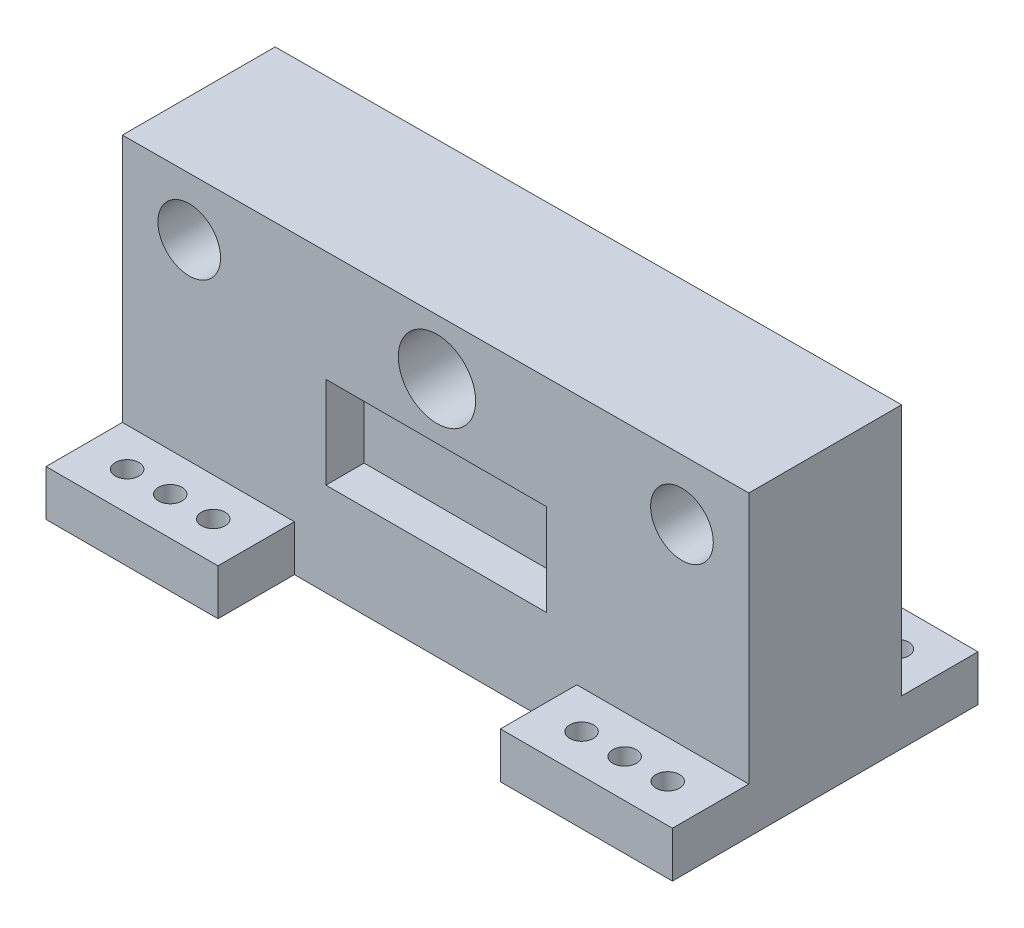
SolidWorks part; units mm, degrees
ref_plane "Спереди" through (0, 0, 0) normal (0, 0, 1) x (1, 0, 0)
ref_plane "Сверху" through (0, 0, 0) normal (0, 1, 0) x (1, 0, 0)
ref_plane "Справа" through (0, 0, 0) normal (1, 0, 0) x (0, 0, -1)
other "Configuration Table"
sketch "Эскиз1" plane through (0, 0, 0) normal (0, 1, 0) x (1, 0, 0)
  line L0 (-41, 0) -> (48.3448, 0) construction
  line L1 (-41, -10) -> (41, -10)
  line L2 (-41, -10) -> (-41, 10)
  line L3 (-41, 10) -> (41, 10)
  line L4 (41, -10) -> (41, 10)
  line L5 (-41, -10) -> (41, 10) construction
  line L6 (-41, 10) -> (41, -10) construction
  line L7 (-41, 10) -> (-41, 24.6591) construction
  line L12 (-41, 15) -> (-14.4824, 15) construction
  line L13 (-41, 10) -> (-18.4858, 10)
  line L14 (-41, 10) -> (-41, 20)
  line L15 (-41, 20) -> (-18.4858, 20)
  line L16 (-18.4858, 10) -> (-18.4858, 20)
  line L17 (-29.7429, 20) -> (-29.7429, 10) construction
  line L18 (-32.5594, 10) -> (-32.5594, 20) construction
  line L19 (0, 10) -> (0, 28.7257) construction
  line L20 (29.7429, 20) -> (29.7429, 10) construction
  line L21 (32.5594, 10) -> (32.5594, 20) construction
  line L22 (41, 20) -> (18.4858, 20)
  line L23 (18.4858, 10) -> (18.4858, 20)
  line L24 (41, 10) -> (18.4858, 10)
  line L25 (41, 10) -> (41, 20)
  line L26 (-32.5594, -10) -> (-32.5594, -20) construction
  line L27 (-29.7429, -20) -> (-29.7429, -10) construction
  line L28 (-18.4858, -10) -> (-18.4858, -20)
  line L29 (-41, -20) -> (-18.4858, -20)
  line L30 (-41, -10) -> (-41, -20)
  line L31 (-41, -10) -> (-18.4858, -10)
  line L32 (32.5594, -10) -> (32.5594, -20) construction
  line L33 (29.7429, -20) -> (29.7429, -10) construction
  line L34 (41, -10) -> (41, -20)
  line L35 (41, -10) -> (18.4858, -10)
  line L36 (18.4858, -10) -> (18.4858, -20)
  line L37 (41, -20) -> (18.4858, -20)
  circle A3 centre (-41, 15) radius 5.6206 construction
  circle A4 centre (-35.3794, 15) radius 1.55
  circle A5 centre (-24.1064, 15) radius 1.55
  circle A6 centre (-35.3794, 15) radius 2.82 construction
  circle A7 centre (-29.7394, 15) radius 1.55
  circle A8 centre (35.3794, 15) radius 2.82 construction
  circle A9 centre (29.7394, 15) radius 1.55
  circle A10 centre (24.1064, 15) radius 1.55
  circle A11 centre (35.3794, 15) radius 1.55
  circle A12 centre (-35.3794, -15) radius 2.82 construction
  circle A13 centre (-41, -15) radius 5.6206 construction
  circle A14 centre (-29.7394, -15) radius 1.55
  circle A15 centre (-24.1064, -15) radius 1.55
  circle A16 centre (-35.3794, -15) radius 1.55
  circle A17 centre (35.3794, -15) radius 2.82 construction
  circle A18 centre (35.3794, -15) radius 1.55
  circle A19 centre (24.1064, -15) radius 1.55
  circle A20 centre (29.7394, -15) radius 1.55
  point P0 (0, 0)
  point P27 (-32.5594, 15)
  point P42 (32.5594, 15)
  point P62 (-32.5594, -15)
  point P77 (32.5594, -15)
extrude "Бобышка-Вытянуть3" add sketch "Эскиз1" along normal blind 6 contours L3 L16 L15 L14 A5 A4 A7 | L1 L4 L3 L2 | L1 L30 L29 L28 A14 A15 A16 | L37 L34 L1 L36 A19 A18 A20 | L3 L25 L22 L23 A9 A10 A11
sketch "Эскиз3" plane through (0, 6, 0) normal (0, 1, 0) x (1, 0, 0)
  line L0 (-41, -20) -> (-41, 20) construction
  line L1 (41, 10) -> (-41, 10)
  line L2 (41, 10) -> (41, -10)
  line L3 (41, -10) -> (-41, -10)
  line L4 (-41, 10) -> (-41, -10)
  line L5 (41, 10) -> (-41, -10) construction
  line L6 (41, -10) -> (-41, 10) construction
  point P0 (0, 0)
extrude "Бобышка-Вытянуть4" add sketch "Эскиз3" along normal up to surface (49 mm away)
sketch "Эскиз5" plane through (0, 0, 10) normal (0, 0, 1) x (1, 0, 0)
  line L0 (0, 0) -> (0, 59.757) construction
  line L1 (-18.4858, 0) -> (18.4858, 0) construction
  circle A1 centre (32.25, 31.0726) radius 4.1
  circle A2 centre (-32.25, 31.0726) radius 4.1
extrude "Вырез-Вытянуть2" cut sketch "Эскиз5" against normal blind 15
sketch "Эскиз6" plane through (0, 0, 10) normal (0, 0, 1) x (1, 0, 0)
  circle A0 centre (0.1787, 31.5226) radius 5.06
extrude "Вырез-Вытянуть3" cut sketch "Эскиз6" against normal blind 15
sketch "Эскиз4" plane through (0, 0, -10) normal (0, 0, -1) x (-1, 0, 0)
  line L0 (23.5, 12.9525) -> (23.5, 55) construction
  line L1 (-23.5, 55) -> (23.5, 55)
  line L6 (41, 39) -> (41, 38.5726)
  line L8 (23.5, 39) -> (23.5, 39.0059)
  line L9 (41, 55) -> (41, 6) construction
  line L10 (-41, 55) -> (41, 55)
  line L11 (-41, 55) -> (-41, 39)
  line L13 (41, 55) -> (41, 39)
  line L15 (0, 0) -> (0, 55) construction
  line L16 (-41, 39) -> (41, 38.5726)
extrude "Вырез-Вытянуть4" cut sketch "Эскиз4" against normal through all both and the other way through all
sketch "Эскиз7" plane through (0, 0, 10) normal (0, 0, 1) x (1, 0, 0)
  line L0 (41, 39) -> (41, 6) construction
  line L1 (-41, 6) -> (41, 6) construction
  line L2 (-41, 6) -> (-41, 12.2085) construction
  line L3 (-41, 12.2085) -> (41, 12.2085) construction
  line L4 (41, 6) -> (41, 12.2085) construction
  line L6 (-14.3607, 12.2085) -> (14.4837, 12.2085)
  line L7 (-14.3607, 12.2085) -> (-14.3607, 24.2085)
  line L8 (-14.3607, 24.2085) -> (14.4837, 24.2085)
  line L9 (14.4837, 12.2085) -> (14.4837, 24.2085)
extrude "Вырез-Вытянуть5" cut sketch "Эскиз7" against normal blind 5
